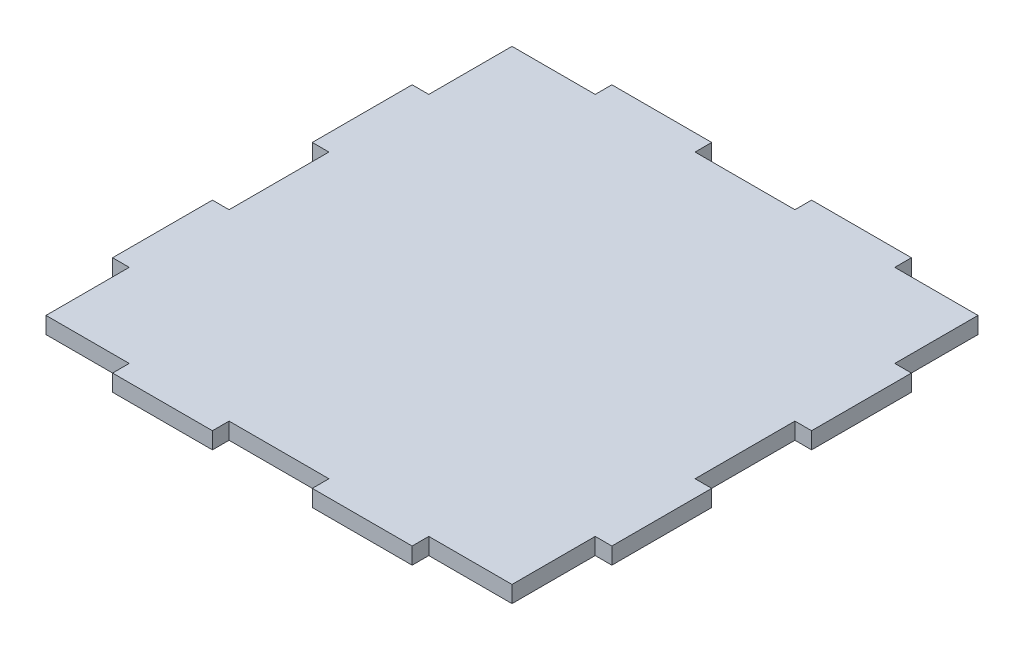
SolidWorks part; units mm, degrees
ref_plane "Front Plane" through (0, 0, 0) normal (0, 0, 1) x (1, 0, 0)
ref_plane "Top Plane" through (0, 0, 0) normal (0, 1, 0) x (1, 0, 0)
ref_plane "Right Plane" through (0, 0, 0) normal (1, 0, 0) x (0, 0, -1)
sketch "Sketch1" plane through (0, 0, 0) normal (0, 1, 0) x (1, 0, 0)
  line L0 (-27, -45) -> (-27, -42)
  line L1 (-45, -45) -> (45, -45)
  line L2 (-45, -45) -> (-45, 45)
  line L3 (-45, 45) -> (45, 45)
  line L4 (45, -45) -> (45, 45)
  line L5 (-45, -45) -> (45, 45) construction
  line L6 (-45, 45) -> (45, -45) construction
  line L7 (-27, -42) -> (-42, -42)
  line L8 (-42, -42) -> (-42, -27)
  line L9 (-42, -27) -> (-45, -27)
  line L10 (-45, -9) -> (-42, -9)
  line L11 (-42, -9) -> (-42, 9)
  line L12 (-42, 9) -> (-45, 9)
  line L13 (-45, 27) -> (-42, 27)
  line L14 (-42, 27) -> (-42, 42)
  line L15 (-42, 42) -> (-27, 42)
  line L16 (-27, 42) -> (-27, 45)
  line L17 (-9, 45) -> (-9, 42)
  line L18 (-9, 42) -> (9, 42)
  line L19 (9, 42) -> (9, 45)
  line L20 (27, 45) -> (27, 42)
  line L21 (27, 42) -> (42, 42)
  line L22 (42, 42) -> (42, 27)
  line L23 (42, 27) -> (45, 27)
  line L24 (45, 9) -> (42, 9)
  line L25 (42, 9) -> (42, -9)
  line L26 (42, -9) -> (45, -9)
  line L27 (45, -27) -> (42, -27)
  line L28 (42, -27) -> (42, -42)
  line L29 (42, -42) -> (27, -42)
  line L30 (27, -42) -> (27, -45)
  line L31 (9, -45) -> (9, -42)
  line L32 (9, -42) -> (-9, -42)
  line L33 (-9, -42) -> (-9, -45)
  point P0 (0, 0)
  dimension "D1" = 90
  dimension "D2" = 90
  dimension "D3" = 18
  dimension "D4" = 18
  dimension "D5" = 18
  dimension "D6" = 18
  dimension "D7" = 18
  dimension "D8" = 18
  dimension "D9" = 18
  dimension "D10" = 18
  dimension "D11" = 18
  dimension "D12" = 18
  dimension "D13" = 18
  dimension "D14" = 18
  dimension "D15" = 3
  dimension "D16" = 3
  dimension "D17" = 3
  dimension "D18" = 3
  dimension "D19" = 3
  dimension "D20" = 3
  dimension "D21" = 3
  dimension "D22" = 18
  dimension "D23" = 18
extrude "Boss-Extrude1" add sketch "Sketch1" along normal blind 3 contours L33 L32 L31 L1 L30 L29 L28 L27 L4 L26 L25 L24 L23 L22 L21 L20 L3 L19 L18 L17 L16 L15 L14 L13 L2 L12 L11 L10 L9 L8 L7 L0
